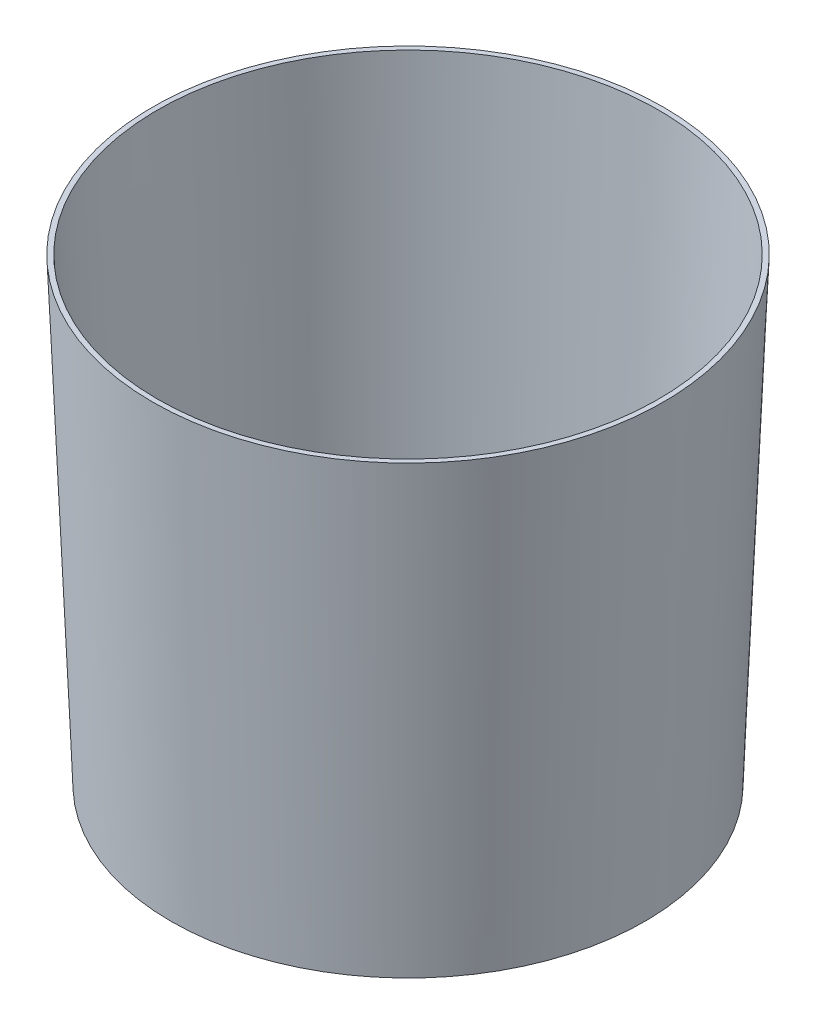
SolidWorks part; units mm, degrees
ref_plane "Front Plane" through (0, 0, 0) normal (0, 0, 1) x (1, 0, 0)
ref_plane "Top Plane" through (0, 0, 0) normal (0, 1, 0) x (1, 0, 0)
ref_plane "Right Plane" through (0, 0, 0) normal (1, 0, 0) x (0, 0, -1)
sketch "Sketch1" plane through (0, 0, 0) normal (0, 1, 0) x (1, 0, 0)
  circle A0 centre (0, 0) radius 96
  dimension "D1" = 192
ref_plane "Plane1" through (0, 186, 0) normal (0, 1, 0) x (1, 0, 0)
sketch "Sketch2" plane through (0, 186, 0) normal (0, 1, 0) x (1, 0, 0)
  circle A0 centre (0, 0) radius 103.5
  dimension "D1" = 207
loft "Loft1" add profiles "Sketch1", "Sketch2"
shell "Shell1" thickness 2
